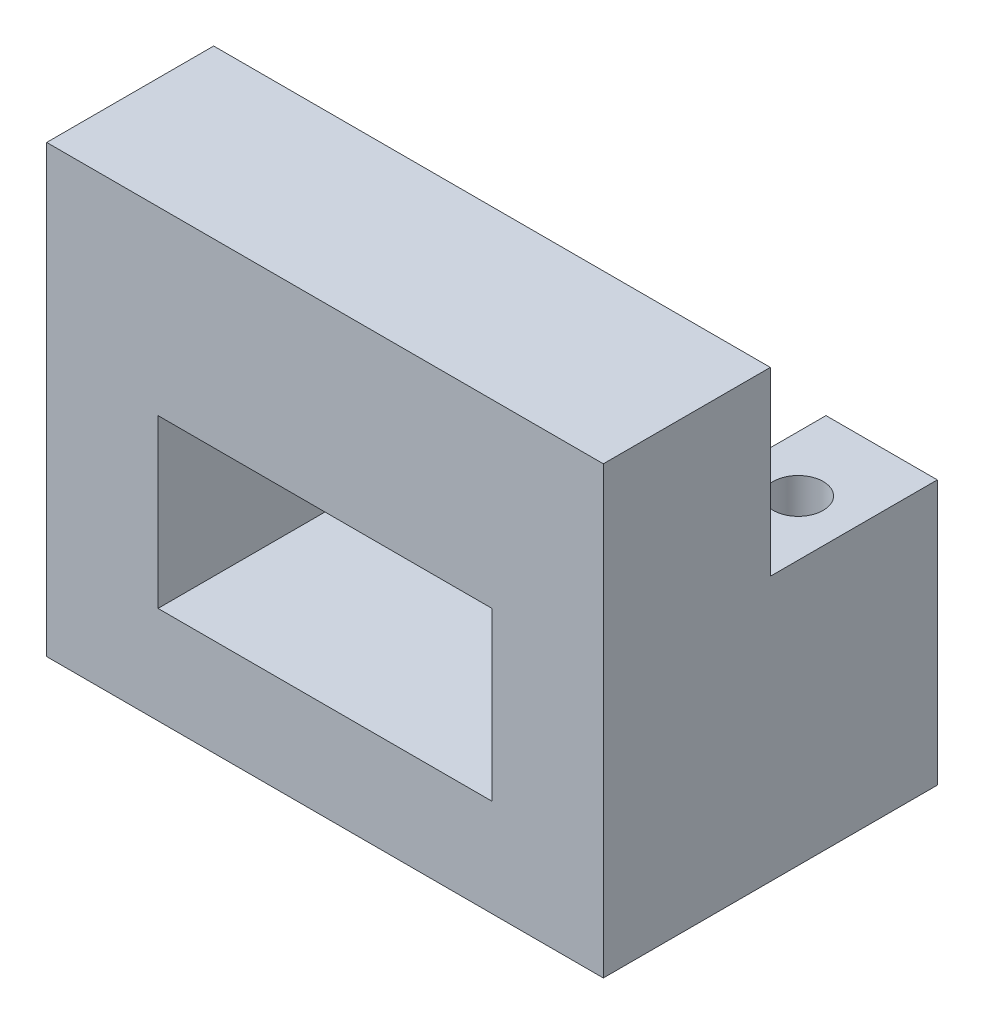
SolidWorks part; units mm, degrees
ref_plane "前视基准面" through (0, 0, 0) normal (0, 0, 1) x (1, 0, 0)
ref_plane "上视基准面" through (0, 0, 0) normal (0, 1, 0) x (1, 0, 0)
ref_plane "右视基准面" through (0, 0, 0) normal (1, 0, 0) x (0, 0, -1)
sketch "草图1" plane through (0, 0, 0) normal (0, 0, 1) x (1, 0, 0)
  line L1 (-50, 40) -> (50, 40)
  line L2 (-50, 40) -> (-50, -40)
  line L3 (-50, -40) -> (50, -40)
  line L4 (50, 40) -> (50, -40)
  line L5 (-50, 40) -> (50, -40) construction
  line L6 (-50, -40) -> (50, 40) construction
  point P0 (0, 0)
  dimension "D1" = 80
  dimension "D2" = 100
extrude "凸台-拉伸1" add sketch "草图1" along normal mid plane 30
sketch "草图4" plane through (0, 0, -15) normal (0, 0, 1) x (1, 0, 0)
  line L0 (-50, 40) -> (-50, -40) construction
  line L1 (50, -40) -> (-50, -40)
  line L2 (50, -40) -> (50, 7.5)
  line L3 (50, 7.5) -> (-50, 7.5)
  line L4 (-50, -40) -> (-50, 7.5)
  dimension "D1" = 47.5
extrude "凸台-拉伸2" add sketch "草图4" against normal blind 30
sketch "草图2" plane through (0, 0, -15) normal (0, 0, -1) x (-1, 0, 0)
  line L1 (30, -22.5) -> (-30, -22.5)
  line L2 (30, -22.5) -> (30, 7.5)
  line L3 (30, 7.5) -> (-30, 7.5)
  line L4 (-30, -22.5) -> (-30, 7.5)
  line L5 (30, -22.5) -> (-30, 7.5) construction
  line L6 (30, 7.5) -> (-30, -22.5) construction
  point P0 (0, -7.5)
  point P6 (0, 0)
  point P7 (0, -7.5)
  dimension "D1" = 30
  dimension "D2" = 60
extrude "切除-拉伸1" cut sketch "草图2" against normal mid plane 109
sketch "草图5" plane through (0, -40, 0) normal (0, -1, 0) x (1, 0, 0)
  line L0 (0, 0) -> (0, -45) construction
  line L1 (-50, -45) -> (50, -45) construction
  line L2 (-50, 15) -> (-50, -45) construction
  circle A0 centre (-40, -30) radius 4.5
  circle A1 centre (40, -30) radius 4.5
  dimension "D1" = 9
  dimension "D2" = 15
  dimension "D3" = 10
extrude "切除-拉伸2" cut sketch "草图5" against normal through all
equation "\"零件重量\"= \"SW-质量\""
